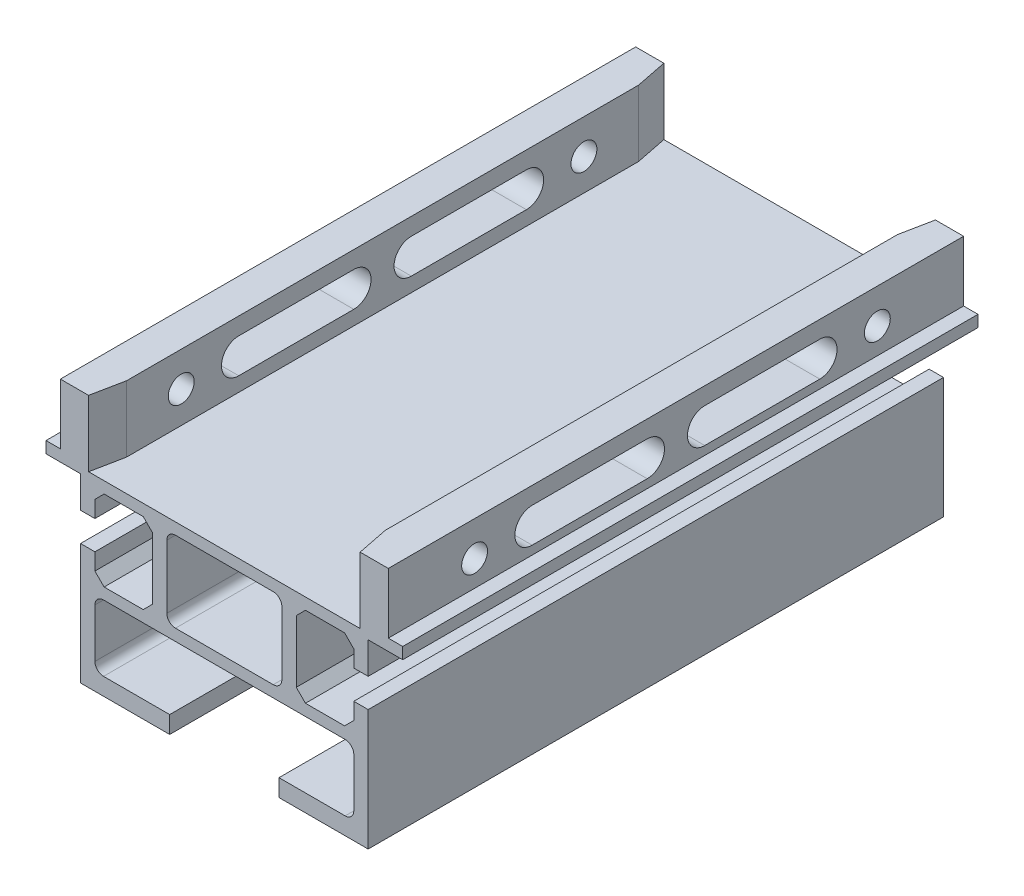
SolidWorks part; units mm, degrees
ref_plane "Piano frontale" through (0, 0, 0) normal (0, 0, 1) x (1, 0, 0)
ref_plane "Piano superiore" through (0, 0, 0) normal (0, 1, 0) x (1, 0, 0)
ref_plane "Piano destro" through (0, 0, 0) normal (1, 0, 0) x (0, 0, -1)
sketch "Schizzo1" plane through (0, 0, 0) normal (0, 0, 1) x (1, 0, 0)
  line L0 (0, 0) -> (15.5, 0)
  line L1 (15.5, 0) -> (15.5, 21)
  line L2 (15.5, 21) -> (13, 21)
  line L3 (13, 21) -> (13, 16.5)
  line L4 (13, 16.5) -> (3, 16.5)
  line L5 (3, 16.5) -> (3, 30.5)
  line L6 (3, 30.5) -> (13, 30.5)
  line L7 (13, 30.5) -> (13, 26)
  line L8 (13, 26) -> (15.5, 26)
  line L9 (15.5, 26) -> (15.5, 31.5)
  line L11 (19, 33.5) -> (19, 44)
  line L12 (19, 44) -> (13, 44)
  line L13 (13, 44) -> (13, 32.5)
  line L14 (13, 32.5) -> (-32, 32.5)
  line L15 (-32, 32.5) -> (-32, 44)
  line L16 (-32, 44) -> (-38, 44)
  line L19 (-34.5, 31.5) -> (-34.5, 26)
  line L20 (-34.5, 26) -> (-32, 26)
  line L21 (-32, 26) -> (-32, 30.5)
  line L22 (-32, 30.5) -> (-22, 30.5)
  line L23 (-22, 30.5) -> (-22, 16.5)
  line L24 (-22, 16.5) -> (-32, 16.5)
  line L25 (-32, 16.5) -> (-32, 21)
  line L26 (-32, 21) -> (-34.5, 21)
  line L27 (-34.5, 21) -> (-34.5, 0)
  line L28 (-34.5, 0) -> (-19, 0)
  line L29 (-19, 0) -> (-19, 3)
  line L30 (-19, 3) -> (-32, 3)
  line L31 (-32, 3) -> (-32, 14.5)
  line L33 (0, 0) -> (0, 3)
  line L34 (0, 3) -> (13, 3)
  line L35 (13, 3) -> (13, 14.5)
  line L36 (13, 14.5) -> (-32, 14.5)
  line L37 (-38, 33.5) -> (-38, 44)
  line L38 (-9.5, 32.5) -> (-9.5, 0) construction
  line L39 (-19.5, 16.5) -> (0.5, 16.5)
  line L40 (0.5, 16.5) -> (0.5, 30.5)
  line L41 (0.5, 30.5) -> (-19.5, 30.5)
  line L42 (-19.5, 30.5) -> (-19.5, 16.5)
  line L43 (19, 33.5) -> (21.5, 33.5)
  line L44 (21.5, 33.5) -> (21.5, 31.5)
  line L45 (21.5, 31.5) -> (15.5, 31.5)
  line L46 (-38, 33.5) -> (-40.5, 33.5)
  line L47 (-40.5, 33.5) -> (-40.5, 31.5)
  line L48 (-40.5, 31.5) -> (-34.5, 31.5)
  point P40 (-9.5, 14.5)
  point P44 (-9.5, 30.5)
  dimension "D2" = 3
  dimension "D3" = 50
  dimension "D4" = 11.5
  dimension "D5" = 2.5
  dimension "D6" = 1
  dimension "D7" = 11.5
  dimension "D8" = 15.5
  dimension "D9" = 14
  dimension "D10" = 10
  dimension "D11" = 6
  dimension "D12" = 2
  dimension "D13" = 5
  dimension "D14" = 1
  dimension "D16" = 2
  dimension "D17" = 21
  dimension "D19" = 6
  dimension "D20" = 2
  dimension "D21" = 45
  dimension "D23" = 2.5
extrude "Estrusione-Estrusione1" add sketch "Schizzo1" along normal blind 100
chamfer "Smusso1" distance 1.6 angle 45 8 edges at (3, 30.5, 50) (13, 30.5, 50) (13, 16.5, 50) (3, 16.5, 50) (-32, 16.5, 50) (-22, 16.5, 50) (-22, 30.5, 50) (-32, 30.5, 50)
fillet "Raccordo1" radius 1.5 8 edges at (0.5, 30.5, 50) (-19.5, 30.5, 50) (-19.5, 16.5, 50) (0.5, 16.5, 50) (13, 3, 50) (13, 14.5, 50) (-32, 14.5, 50) (-32, 3, 50)
chamfer "Smusso2" distance 5.5 angle 11.31 2 edges at (13, 38.25, 100) (-32, 38.25, 100)
chamfer "Smusso3" distance 5.5 angle 11.31 2 edges at (-32, 38.25, 0) (13, 38.25, 0)
hole_wizard "Foro per Vite M4-1" positions "Schizzo2" profile "Schizzo3" hole size "M4" standard "ISO"
sketch "Schizzo2" plane through (19, 0, 0) normal (1, 0, 0) x (0, 0, -1)
  line L0 (0, 33.5) -> (0, 44) construction
  line L1 (-100, 44) -> (0, 44) construction
  line L2 (-85, 38) -> (-15, 38) construction
  line L4 (-100, 33.5) -> (-100, 44) construction
  point P0 (-85, 38)
  point P2 (-15, 38)
  dimension "D1" = 15
  dimension "D2" = 6
  dimension "D3" = 15
sketch "Schizzo3" plane through (19, 38, 85) normal (0, 1, 0) x (0, 0, -1)
  line L0 (0, 0) -> (0, 189.3519)
  line L1 (0, 189.3519) -> (2.25, 188)
  line L2 (2.25, 188) -> (2.25, 0)
  line L5 (2.25, 0) -> (0, 0)
  line L10 (0, 189.3519) -> (-2.25, 188) construction
  line L11 (0, -6.35) -> (0, 107.95) construction
  dimension "Hole Dia." = 4.5
  dimension "Hole Depth" = 188
  dimension "Drill Angle" = 118
sketch "Schizzo4" plane through (19, 0, 0) normal (1, 0, 0) x (0, 0, -1)
  line L0 (-75, 38) -> (-55, 38) construction
  line L1 (-75, 41) -> (-55, 41)
  line L2 (-75, 35) -> (-55, 35)
  line L3 (-45, 38) -> (-25, 38) construction
  line L4 (-45, 41) -> (-25, 41)
  line L5 (-45, 35) -> (-25, 35)
  line L6 (-100, 33.5) -> (-100, 44) construction
  line L7 (-100, 44) -> (0, 44) construction
  line L8 (0, 33.5) -> (0, 44) construction
  arc A0 (-75, 41) -> (-75, 35) centre (-75, 38) ccw
  arc A1 (-55, 35) -> (-55, 41) centre (-55, 38) ccw
  arc A2 (-45, 41) -> (-45, 35) centre (-45, 38) ccw
  arc A3 (-25, 35) -> (-25, 41) centre (-25, 38) ccw
  point P2 (-65, 38)
  point P7 (-35, 38)
  dimension "D2" = 3
  dimension "D1" = 25
  dimension "D3" = 20
  dimension "D4" = 3
  dimension "D5" = 25
extrude "Taglio-Estrusione1" cut sketch "Schizzo4" against normal blind 81
